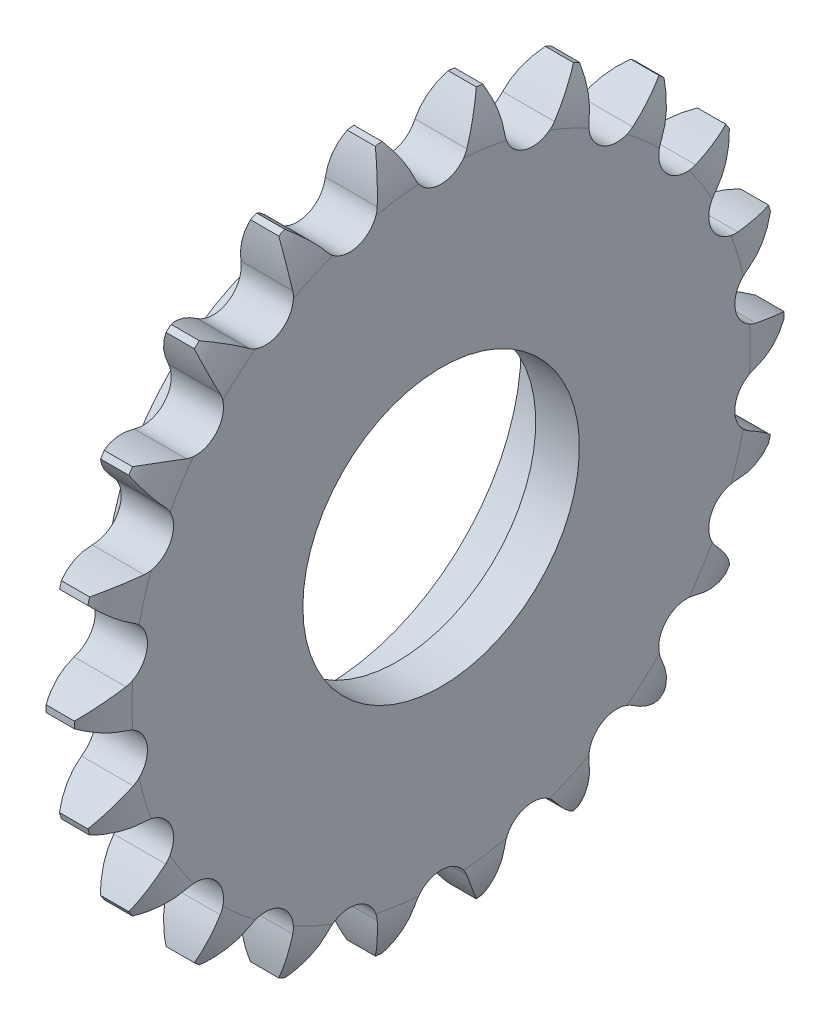
SolidWorks part; units mm, degrees
ref_plane "Plane1" through (0, 0, 0) normal (0, 0, 1) x (1, 0, 0)
ref_plane "Plane2" through (0, 0, 0) normal (0, 1, 0) x (1, 0, 0)
ref_plane "Plane3" through (0, 0, 0) normal (1, 0, 0) x (0, 0, -1)
sketch "Clipboard" plane through (0, 0, 0) normal (0, 1, 0) x (1, 0, 0)
  line L0 (0, 0) -> (29.4381, -11.8938)
  line L1 (-15, 0) -> (100, 0) construction
  line L2 (0, 0) -> (-2.735, 3.0912)
  line L3 (0, 0) -> (-29.6576, 11.3353)
  line L4 (0, 0) -> (2.8743, 1.1613)
  line L5 (0, 0) -> (-37.4781, -13.9782)
  line L6 (0, 0) -> (-14.8882, -10.0451)
  line L7 (-2.735, 3.0912) -> (34.0856, 18.7207)
  line L8 (-76.2, 38.1) -> (-69.8, 38.1)
  line L9 (-74.5857, 46.8566) -> (-73.8247, 47.1033)
  line L10 (-75.3676, 33.2712) -> (-39.6076, 33.2712)
  circle A0 centre (0, 0) radius 9.525
  circle A1 centre (0, 0) radius 75
  circle A2 centre (0, 0) radius 75
  dimension "Dr" = 19.05
  dimension "MHD" = 150
  dimension "Hub_dia" = 150
  dimension "Num_teeth" = 22
  dimension "Pitch" = 31.75
  dimension "Width" = 3.1
  dimension "Side_relief" = 4.1275
  dimension "Side_radius" = 31.75
  dimension "Overall_len" = 40
  dimension "Show_teeth" = 22
  dimension "Thickness" = 17.96
  dimension "OAL" = 40.0005
  dimension "T_dim" = 6.4
  dimension "Fillet_rad" = 0.8
  dimension "Face_width" = 17.96
  dimension "Num_strands" = 1
  dimension "Transv_pitch" = 35.76
  dimension "Plate_wid" = 30.18
sketch "BasProSke" plane through (0, 0, 0) normal (0, 1, 0) x (1, 0, 0)
  line L0 (-10, 0) -> (60, 0) construction
  line L1 (0, 0) -> (0, 106.2128)
  line L2 (0, 0) -> (17.96, 0)
  line L3 (17.96, 0) -> (17.96, 106.2128)
  line L4 (13.8325, 121.8672) -> (4.1275, 121.8672)
  arc A0 (0, 106.2128) -> (4.1275, 121.8672) centre (31.75, 106.2128) cw
  arc A1 (17.96, 106.2128) -> (13.8325, 121.8672) centre (-13.79, 106.2128) ccw
  dimension "Thickness" = 17.96
  dimension "D1" = 31.75
  dimension "G1" = 4.1275
  dimension "G2" = 4.1275
  dimension "Diameter" = 243.7344
revolve "Base-Revolve" add sketch "BasProSke" angle 360 about L0
sketch "TooCutSke" plane through (0, 0, 0) normal (1, 0, 0) x (0, 0, -1)
  line L0 (0, 111.6437) -> (8.9169, 108.0328) construction
  line L1 (0, 0) -> (0, 107) construction
  line L2 (0, 111.6437) -> (-10, 111.6437) construction
  line L3 (0, 111.6437) -> (-8.9169, 108.0328) construction
  arc A0 (8.9169, 108.0328) -> (16.5553, 121.2421) centre (59.7696, 87.4401) cw
  arc A1 (8.9169, 108.0328) -> (-8.9169, 108.0328) centre (0, 111.6437) cw
  arc A2 (-8.9169, 108.0328) -> (-16.5553, 121.2421) centre (-59.7696, 87.4401) ccw
  arc A3 (16.5553, 121.2421) -> (-16.5553, 121.2421) centre (0, 0) ccw
  dimension "R1" = 9.6203
  dimension "R2" = 54.864
  dimension "Overcut" = 122.3672
  dimension "Seat_radius" = 111.6437
  dimension "X" = 135.909
extrude "ToothCut" cut sketch "TooCutSke" along normal through all
pattern_circular "TeethCuts" count 22 every 16.364 about axis through (-10, 0, 0) along (1, 0, 0) of "ToothCut"
sketch "HubNeaOneSke" plane through (0, 0, 0) normal (-1, 0, 0) x (0, 0, 1)
  circle A0 centre (0, 0) radius 75
  dimension "Diameter" = 150
extrude "HubNearOne" add sketch "HubNeaOneSke" along normal blind 22.0405
fillet "HubNearOneFillet" radius 0.8 1 edges at (0, 0, -75)
sketch "HubNeaBotSke" plane through (0, 0, 0) normal (-1, 0, 0) x (0, 0, 1)
  circle A0 centre (0, 0) radius 75
  dimension "Diameter" = 150
extrude "HubNearBoth" [suppressed] add sketch "HubNeaBotSke" along normal blind 11.0203
fillet "HubNearBothFillet" [suppressed] radius 0.8
ref_plane "FarPln" through (17.96, 0, 0) normal (1, 0, 0) x (0, 0, -1)
sketch "HubFarSke" plane through (17.96, 0, 0) normal (1, 0, 0) x (0, 0, -1)
  circle A0 centre (0, 0) radius 75
  dimension "Diameter" = 150
extrude "HubFar" [suppressed] add sketch "HubFarSke" along normal blind 11.0203
fillet "HubFarFillet" [suppressed] radius 0.8
sketch "BorSke" plane through (0, 0, 0) normal (1, 0, 0) x (0, 0, -1)
  circle A0 centre (0, 0) radius 47.5
  dimension "Diameter" = 95
extrude "Bore" cut sketch "BorSke" along normal mid plane 80.001
sketch "KeySke" plane through (0, 0, 0) normal (1, 0, 0) x (0, 0, -1)
  line L0 (-14, 0) -> (-14, 53.9)
  line L1 (-14, 53.9) -> (14, 53.9)
  line L2 (14, 53.9) -> (14, 0)
  line L3 (0, 0) -> (0, 34) construction
  line L4 (-14, 0) -> (14, 0)
  dimension "Offset" = 53.9
  dimension "Width" = 28
extrude "Keyway" [suppressed] cut sketch "KeySke" along normal mid plane 80.001
pattern_circular "Keyway2" [suppressed] count 2 every 90 about axis through (-10, 0, 0) along (1, 0, 0)
sketch "Schizzo1" plane through (-22.0405, 0, 0) normal (-1, 0, 0) x (0, 0, 1)
  circle A0 centre (0, 0) radius 67.5
extrude "Taglio-Estrusione1" cut sketch "Schizzo1" against normal blind 25
equation "' \"Pitch@Clipboard\" = 12.7"
equation "' \"Num_strands@Clipboard\" = 1"
equation "' \"Num_teeth@Clipboard\" = 9"
equation "' \"Hub_dia@Clipboard\" = 50"
equation "' \"Overall_len@Clipboard\" = 3"
equation "' \"Diameter@BorSke\" = 12"
equation "' \"T_dim@Clipboard\" = 1"
equation "' \"Width@KeySke\" = 2"
equation "' \"Dr@Clipboard\" = 8.51"
equation "' \"Face_width@Clipboard\" = 7.2"
equation "' \"Side_radius@Clipboard\" = 12.7"
equation "' \"Side_relief@Clipboard\" = 1.27"
equation "' \"Transv_pitch@Clipboard\" = 13.92"
equation "' \"Show_teeth@Clipboard\" = 9"
equation "' \"Fillet_rad@Clipboard\" = 0.6"
equation "' \"Plate_wid@Clipboard\" = 11.8"
equation "\"Num_teeth@Clipboard\" = int( \"Num_teeth@Clipboard\" )"
equation "\"Num_teeth@Clipboard\" = ((sgn( \"Num_teeth@Clipboard\" - 5.0)+1)*( \"Num_teeth@Clipboard\" - 5.0))/2 +5.0"
equation "\"Num_teeth@Clipboard\" = ((sgn( \"Num_teeth@Clipboard\" - 200.0)-1)*( \"Num_teeth@Clipboard\" - 200.0))/-2 +200.0"
equation "\"MHD@Clipboard\" = \"Pitch@Clipboard\" * (1.0 / tan(3.14159265 / \"Num_teeth@Clipboard\" )) - 1.04 * \"Plate_wid@Clipboard\" - 0.76"
equation "\"Thickness@Clipboard\"  = \"Face_width@Clipboard\" + (\"Num_strands@Clipboard\" - 1) * \"Transv_pitch@Clipboard\""
equation "\"OAL@Clipboard\" = \"Thickness@Clipboard\" + 2 * \"Fillet_rad@Clipboard\" + 1"
equation "\"MHD@Clipboard\" = ((sgn( \"MHD@Clipboard\" - \"Hub_dia@Clipboard\" )-1)*( \"MHD@Clipboard\" - \"Hub_dia@Clipboard\" ))/-2+ \"Hub_dia@Clipboard\""
equation "\"OAL@Clipboard\" = ((sgn( \"OAL@Clipboard\" - \"Overall_len@Clipboard\" )+1)*( \"OAL@Clipboard\" - \"Overall_len@Clipboard\" ))/2 + \"Overall_len@Clipboard\" + 0.0005"
equation "\"Num_teeth@TeethCuts\" = int( \"Show_teeth@Clipboard\" ) + 1"
equation "\"Num_teeth@TeethCuts\" = ((sgn( \"Num_teeth@TeethCuts\" - \"Num_teeth@Clipboard\" )-1)*( \"Num_teeth@TeethCuts\" - \"Num_teeth@Clipboard\" ))/-2+ \"Num_teeth@Clipboard\""
equation "\"Num_teeth@TeethCuts\" = ((sgn( \"Num_teeth@TeethCuts\" - 2.0)+1)*( \"Num_teeth@TeethCuts\" - 2.0))/2 +2.0"
equation "\"Angle@TeethCuts\" = 360.0 / \"Num_teeth@Clipboard\""
equation "\"Seat_radius@TooCutSke\" = ( \"Pitch@Clipboard\" / 2.0) / sin(3.14159265 / \"Num_teeth@Clipboard\" ) - \"Dr@Clipboard\" / 2.0 + \"Dr@Clipboard\" * 0.505"
equation "\"R1@TooCutSke\"  = \"Dr@Clipboard\" * 0.505"
equation "\"X@TooCutSke\" = 140.0 - (90.0 / \"Num_teeth@Clipboard\")"
equation "\"R2@TooCutSke\" = 0.12 * \"Dr@Clipboard\" * ( \"Num_teeth@Clipboard\" + 2.0)"
equation "\"Overcut@TooCutSke\" = 0.5 + 0.625 * \"Pitch@Clipboard\" - 0.5 * \"Dr@Clipboard\"  +  \"Pitch@Clipboard\" / 2.0 / sin(3.14159265 / \"Num_teeth@Clipboard\" )"
equation "\"Diameter@BasProSke\" = 2.0 * ( 0.625 * \"Pitch@Clipboard\" - 0.5 * \"Dr@Clipboard\"  +  \"Pitch@Clipboard\" / 2.0 / sin(3.14159265 / \"Num_teeth@Clipboard\" ))"
equation "\"Thickness@BasProSke\"  = \"Thickness@Clipboard\""
equation "\"G1@BasProSke\" =  \"Side_relief@Clipboard\""
equation "\"G2@BasProSke\" =  \"Side_relief@Clipboard\""
equation "\"D1@BasProSke\" =  \"Side_radius@Clipboard\""
equation "\"Diameter@HubNeaOneSke\" = \"MHD@Clipboard\""
equation "\"Length@HubNearOne\" = \"OAL@Clipboard\" - \"Thickness@BasProSke\""
equation "\"Diameter@HubNeaBotSke\" = \"MHD@Clipboard\""
equation "\"Length@HubNearBoth\" = ( \"OAL@Clipboard\" - \"Thickness@BasProSke\" ) / 2.0"
equation "\"D1@HubNearOneFillet\" = \"Fillet_rad@Clipboard\""
equation "\"D1@HubNearBothFillet\" = \"Fillet_rad@Clipboard\""
equation "\"Thickness@FarPln\" = \"Thickness@BasProSke\""
equation "\"Diameter@HubFarSke\" = \"MHD@Clipboard\""
equation "\"Length@HubFar\" = ( \"OAL@Clipboard\" - \"Thickness@BasProSke\" ) / 2.0"
equation "\"D1@HubFarFillet\" = \"Fillet_rad@Clipboard\""
equation "\"D1@Bore\" = \"OAL@Clipboard\" * 2.0"
equation "\"D1@Keyway\" = \"OAL@Clipboard\" * 2.0"
equation "\"Offset@KeySke\" = \"T_dim@Clipboard\" + \"Diameter@BorSke\" / 2.0"
